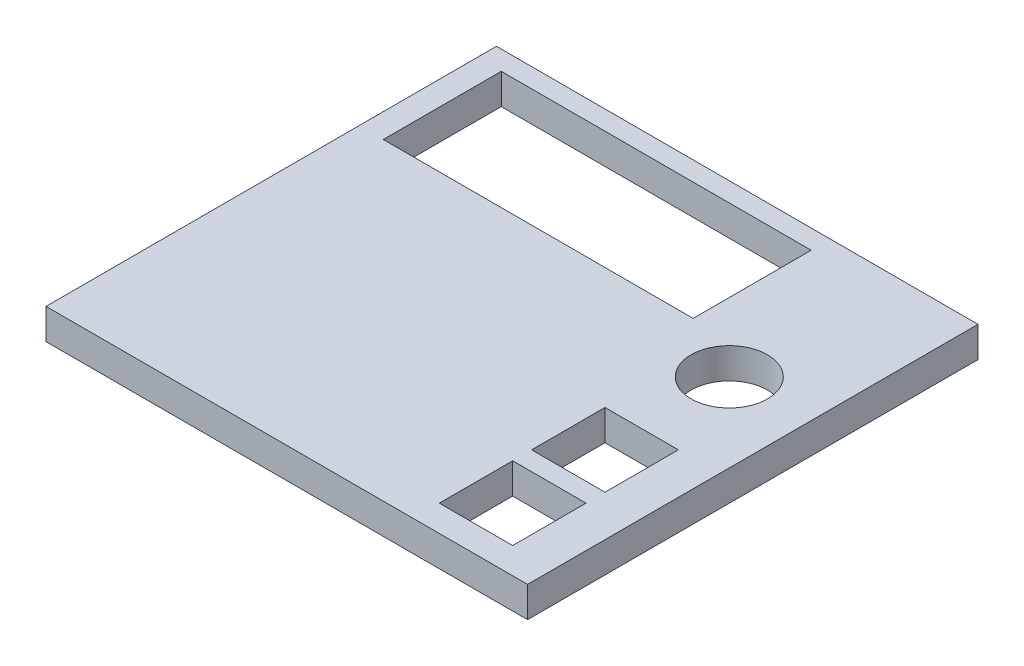
SolidWorks part; units mm, degrees
ref_plane "Front Plane" through (0, 0, 0) normal (0, 0, 1) x (1, 0, 0)
ref_plane "Top Plane" through (0, 0, 0) normal (0, 1, 0) x (1, 0, 0)
ref_plane "Right Plane" through (0, 0, 0) normal (1, 0, 0) x (0, 0, -1)
sketch "Sketch1" plane through (0, 0, 0) normal (0, 1, 0) x (1, 0, 0)
  line L1 (-31.1631, 9.5386) -> (47.5769, 9.5386)
  line L2 (-31.1631, 9.5386) -> (-31.1631, -64.1214)
  line L3 (-31.1631, -64.1214) -> (47.5769, -64.1214)
  line L4 (47.5769, 9.5386) -> (47.5769, -64.1214)
  line L5 (-27.2231, 6.3886) -> (23.4469, 6.3886)
  line L6 (-27.2231, 6.3886) -> (-27.2231, -12.9114)
  line L7 (-27.2231, -12.9114) -> (23.4469, -12.9114)
  line L8 (23.4469, 6.3886) -> (23.4469, -12.9114)
  line L9 (-27.2231, 6.3886) -> (23.4469, -12.9114) construction
  line L10 (-27.2231, -12.9114) -> (23.4469, 6.3886) construction
  line L11 (28.8579, -32.7334) -> (40.8579, -32.7334)
  line L12 (28.8579, -32.7334) -> (28.8579, -44.7334)
  line L13 (28.8579, -44.7334) -> (40.8579, -44.7334)
  line L14 (40.8579, -32.7334) -> (40.8579, -44.7334)
  line L15 (28.8579, -32.7334) -> (40.8579, -44.7334) construction
  line L16 (28.8579, -44.7334) -> (40.8579, -32.7334) construction
  line L17 (28.8579, -47.8334) -> (40.8579, -47.8334)
  line L18 (28.8579, -47.8334) -> (28.8579, -59.8334)
  line L19 (28.8579, -59.8334) -> (40.8579, -59.8334)
  line L20 (40.8579, -47.8334) -> (40.8579, -59.8334)
  line L21 (28.8579, -47.8334) -> (40.8579, -59.8334) construction
  line L22 (28.8579, -59.8334) -> (40.8579, -47.8334) construction
  circle A0 centre (34.6769, -18.2334) radius 6.25
  point P4 (2.2255, -20.5908)
  point P9 (-1.8881, -3.2614)
  point P16 (34.8579, -38.7334)
  point P21 (34.8579, -53.8334)
  point P22 (34.8579, -47.8334)
  dimension "D7" = 12.5
  dimension "D1" = 78.74
  dimension "D2" = 73.66
  dimension "D3" = 50.67
  dimension "D4" = 19.3
  dimension "D5" = 3.15
  dimension "D6" = 3.94
  dimension "D8" = 12
  dimension "D9" = 12
  dimension "D10" = 12
  dimension "D11" = 12
  dimension "D12" = 14.5
  dimension "D13" = 27.772
  dimension "D14" = 6.719
  dimension "D15" = 6.719
  dimension "D16" = 3.1
  dimension "D17" = 12.9
extrude "Boss-Extrude1" add sketch "Sketch1" along normal blind 5
